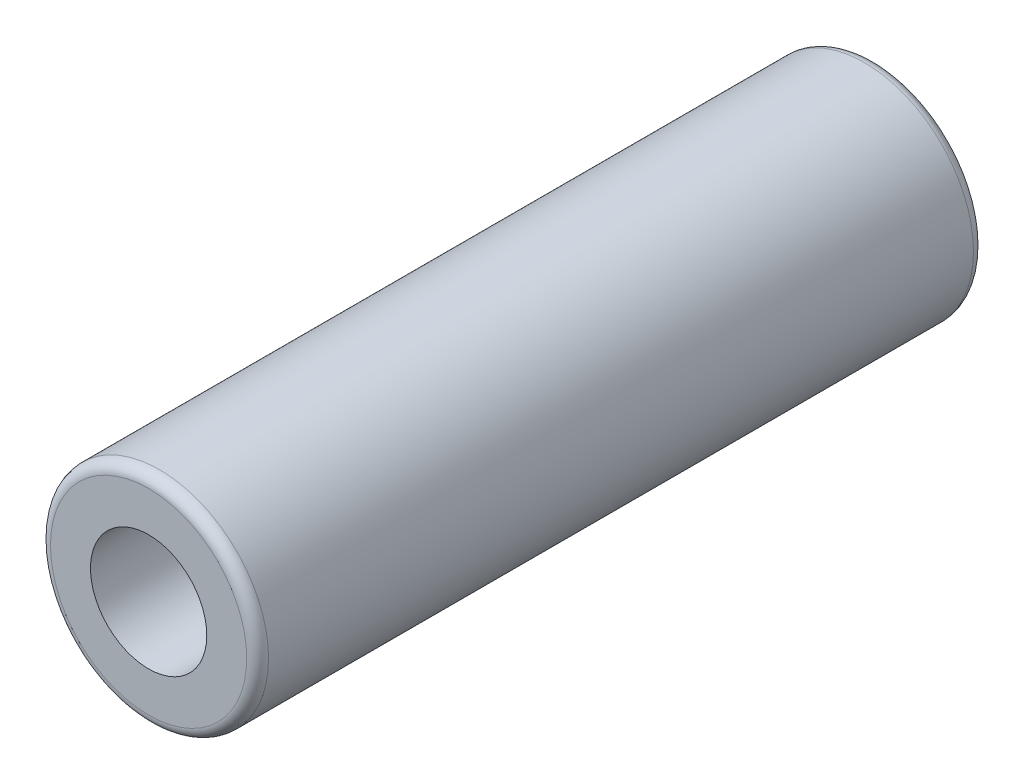
SolidWorks part; units mm, degrees
ref_plane "Front Plane" through (0, 0, 0) normal (0, 0, 1) x (1, 0, 0)
ref_plane "Top Plane" through (0, 0, 0) normal (0, 1, 0) x (1, 0, 0)
ref_plane "Right Plane" through (0, 0, 0) normal (1, 0, 0) x (0, 0, -1)
sketch "Sketch1" plane through (0, 0, 0) normal (0, 0, 1) x (1, 0, 0)
  circle A0 centre (0, 0) radius 3
  circle A1 centre (0, 0) radius 1.6
  dimension "D1" = 6
  dimension "D2" = 3.2
extrude "Boss-Extrude1" add sketch "Sketch1" along normal blind 20
fillet "Fillet1" radius 0.3 2 edges at (3, 0, 0) (3, 0, 20)
